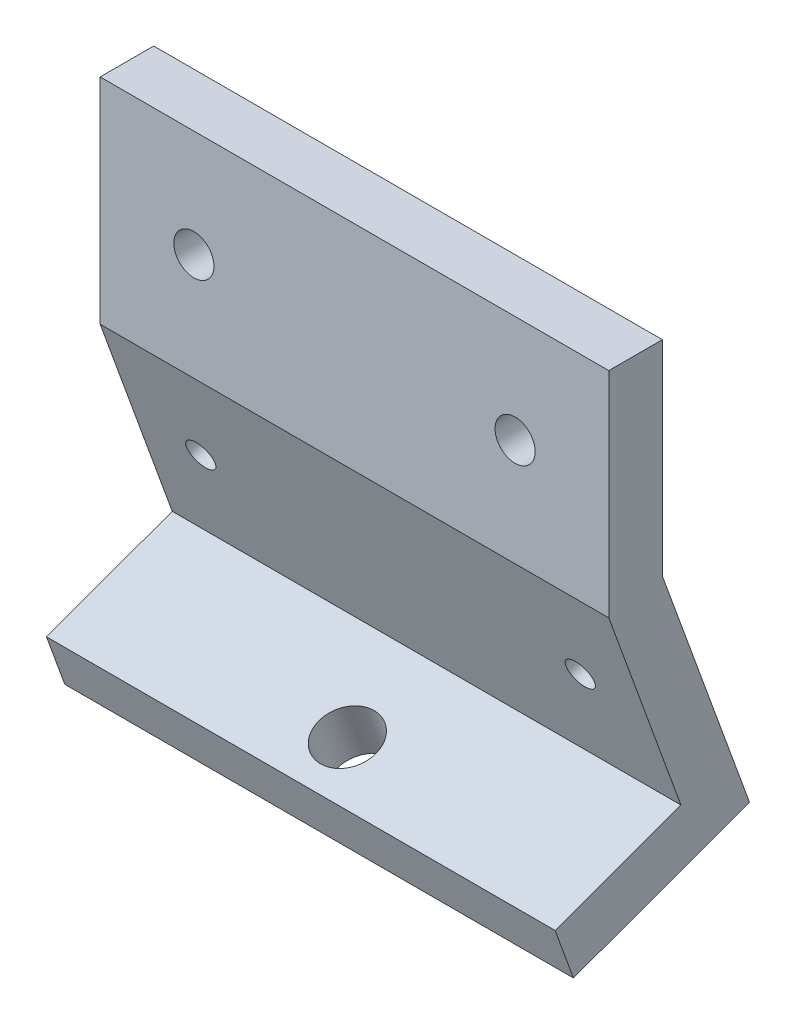
SolidWorks part; units mm, degrees
ref_plane "Front" through (0, 0, 0) normal (0, 0, 1) x (1, 0, 0)
ref_plane "Top" through (0, 0, 0) normal (0, 1, 0) x (1, 0, 0)
ref_plane "Right" through (0, 0, 0) normal (1, 0, 0) x (0, 0, -1)
sketch "Sketch2" plane through (0, 0, 0) normal (1, 0, 0) x (0, 0, -1)
  line L0 (0, 0) -> (0, 25.4)
  line L1 (0, 25.4) -> (6.35, 25.4)
  line L2 (6.35, 25.4) -> (6.35, 1.1197)
  line L3 (6.35, 1.1197) -> (16.6894, -27.2875)
  line L4 (16.6894, -27.2875) -> (-4.1953, -34.8889)
  line L5 (-4.1953, -34.8889) -> (-6.3671, -28.9219)
  line L6 (-6.3671, -28.9219) -> (8.5505, -23.4923)
  line L7 (8.5505, -23.4923) -> (0, 0)
  dimension "D1" = 6.35
  dimension "D2" = 6.35
  dimension "D3" = 6.35
  dimension "D4" = 20
  dimension "D5" = 15.875
  dimension "D6" = 25.4
  dimension "D7" = 25
extrude "Boss-Extrude1" add sketch "Sketch2" along normal mid plane 60.325
hole_wizard "1/4 Clearance Hole1" positions "Sketch5" profile "Sketch6" hole size "1/4" standard "ANSI Inch" end condition up to next
sketch "Sketch5" plane through (0, -23.4923, -8.5505) normal (0, 0.9397, 0.342) x (1, 0, 0)
  line L0 (30.1625, 0) -> (-30.1625, 0) construction
  point P0 (0, -10)
  dimension "D1" = 10
sketch "Sketch6" plane through (0, -26.9125, 0.8464) normal (1, 0, 0) x (0, -0.342, 0.9397)
  line L0 (0, 0) -> (0, 6.35)
  line L1 (0, 6.35) -> (3.3782, 6.35)
  line L2 (3.3782, 6.35) -> (3.3782, 0)
  line L5 (3.3782, 0) -> (0, 0)
  line L11 (0, -6.35) -> (0, 107.95) construction
  dimension "Thru Hole Dia." = 6.7564
  dimension "Thru Hole Depth" = 6.35
hole_wizard "M3 Clearance Hole1" positions "Sketch7" profile "Sketch8" hole size "M3" standard "ANSI Metric" end condition up to next
sketch "Sketch7" plane through (0, 0, 0) normal (0, -0.342, 0.9397) x (1, 0, 0)
  line L0 (22.5, -12.5) -> (-22.5, -12.5) construction
  line L5 (0, -12.5) -> (0, 0) construction
  line L7 (0, -12.5) -> (0, -25) construction
  line L8 (30.1625, -25) -> (-30.1625, -25) construction
  point P0 (-22.5, -12.5)
  point P2 (22.5, -12.5)
  point P8 (0, -12.5)
  dimension "D1" = 45
sketch "Sketch8" plane through (-22.5, -11.7462, -4.2753) normal (1, 0, 0) x (0, -0.9397, -0.342)
  line L0 (0, 0) -> (0, 6.35)
  line L1 (0, 6.35) -> (1.7, 6.35)
  line L2 (1.7, 6.35) -> (1.7, 0)
  line L5 (1.7, 0) -> (0, 0)
  line L11 (0, -6.35) -> (0, 107.95) construction
  dimension "Thru Hole Dia." = 3.4
  dimension "Thru Hole Depth" = 6.35
sketch "Sketch9" plane through (30.1625, 0, 0) normal (1, 0, 0) x (0, 0, -1)
  line L0 (4.2753, -11.7462) -> (-822.9356, -312.8263) construction
  line L1 (0, 0) -> (8.5505, -23.4923) construction
  line L2 (4.2753, -11.7462) -> (-938.5094, 4.7102)
  line L3 (-938.5094, 4.7102) -> (-707.3618, -630.3628)
  line L4 (-707.3618, -630.3628) -> (4.2753, -11.7462)
  point P7 (-822.9356, -312.8263)
  dimension "D1" = 42
hole_wizard "3/16 (0.1875) Diameter Hole2" positions "Sketch12" profile "Sketch13" hole size "3/16" standard "ANSI Inch" end condition up to next
sketch "Sketch12" plane through (0, 0, 0) normal (0, 0, 1) x (1, 0, 0)
  line L0 (-19.05, 12.7) -> (19.05, 12.7) construction
  line L2 (30.1625, 0) -> (-30.1625, 0) construction
  point P0 (-19.05, 12.7)
  point P2 (19.05, 12.7)
  point P9 (0, 12.7)
  dimension "D1" = 12.7
  dimension "D2" = 38.1
sketch "Sketch13" plane through (-19.05, 12.7, 0) normal (1, 0, 0) x (0, -1, 0)
  line L0 (0, 0) -> (0, 6.35)
  line L1 (0, 6.35) -> (2.3812, 6.35)
  line L2 (2.3812, 6.35) -> (2.3812, 0)
  line L5 (2.3812, 0) -> (0, 0)
  line L11 (0, -6.35) -> (0, 107.95) construction
  dimension "Thru Hole Dia." = 4.7625
  dimension "Thru Hole Depth" = 6.35
equation "\"part-thickness\"=0.25"
equation "\"D1@Sketch2\"=\"part-thickness\""
equation "\"D2@Sketch2\"=\"part-thickness\""
equation "\"D3@Sketch2\"=\"part-thickness\""
equation "\"tilt-angle\"= 20"
equation "\"D4@Sketch2\"=\"tilt-angle\""
